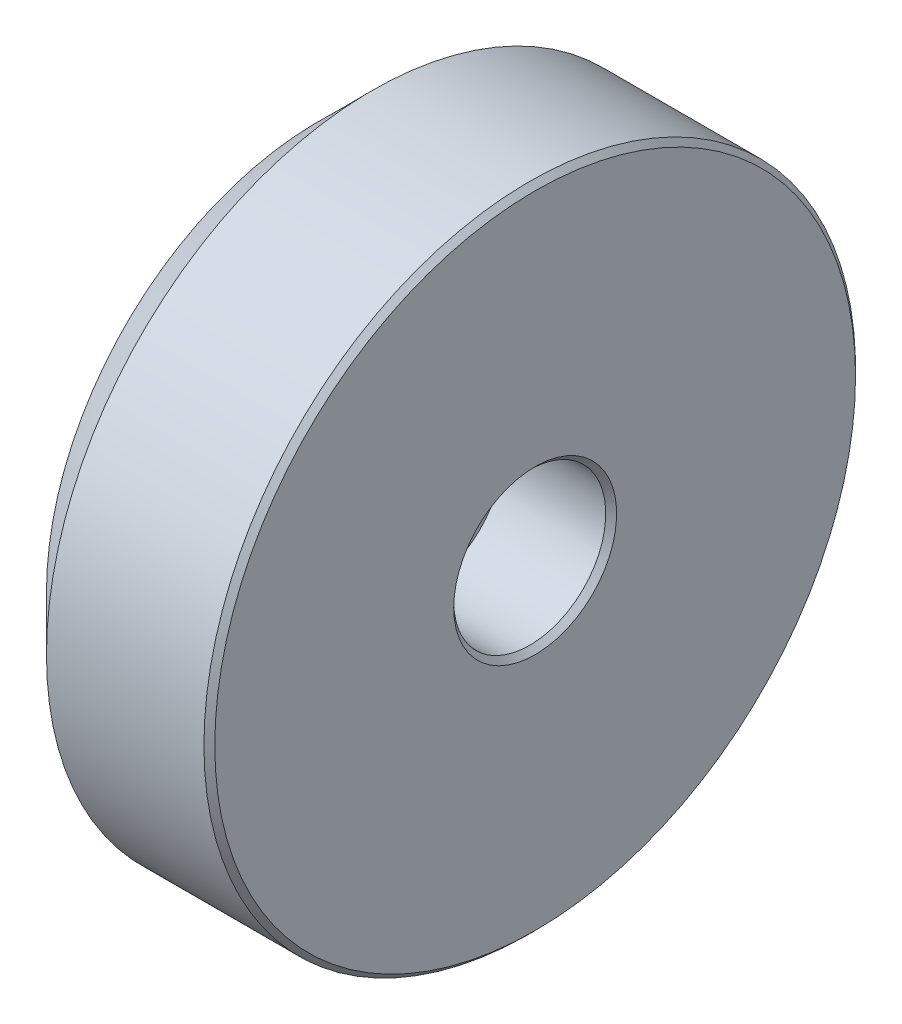
SolidWorks part; units mm, degrees
ref_plane "정면" through (0, 0, 0) normal (0, 0, 1) x (1, 0, 0)
ref_plane "윗면" through (0, 0, 0) normal (0, 1, 0) x (1, 0, 0)
ref_plane "우측면" through (0, 0, 0) normal (1, 0, 0) x (0, 0, -1)
sketch "스케치2" plane through (0, 0, 0) normal (0, 0, 1) x (1, 0, 0)
  line L0 (0, 0) -> (20, 0) construction
  line L1 (0, 0) -> (0, 25)
  line L2 (0, 25) -> (5, 30)
  line L3 (5, 30) -> (20, 30)
  line L4 (20, 30) -> (20, 0)
  line L5 (0, 0) -> (20, 0)
  point P5 (0, 1.182)
  dimension "D1" = 60
  dimension "D2" = 50
  dimension "D3" = 5
  dimension "D4" = 20
revolve "회전1" add sketch "스케치2" angle 360 about L0
sketch "스케치4" plane through (0, 0, 0) normal (0, 0, 1) x (1, 0, 0)
  line L0 (0, 0) -> (20, 0) construction
  line L1 (20, -30) -> (20, 30) construction
  line L2 (20, 7) -> (10, 7)
  line L3 (10, 7) -> (10, 4.5)
  line L4 (10, 4.5) -> (3, 4.5)
  line L5 (3, 4.5) -> (3, 10.25)
  line L6 (3, 10.25) -> (0, 10.25)
  line L7 (0, 25) -> (0, -25) construction
  line L8 (0, 10.25) -> (0, 0)
  line L9 (20, 7) -> (20, 0)
  line L10 (0, 0) -> (20, 0)
  dimension "D1" = 14
  dimension "D2" = 9
  dimension "D3" = 20.5
  dimension "D4" = 3
  dimension "D5" = 7
revolve "컷-회전1" cut sketch "스케치4" angle 360 about L0
chamfer "모따기1" distance 0.5 angle 45 2 edges at (0, 0, 10.25) (20, 0, 7)
chamfer "모따기2" distance 0.5 angle 45 1 edges at (20, 0, 30)
